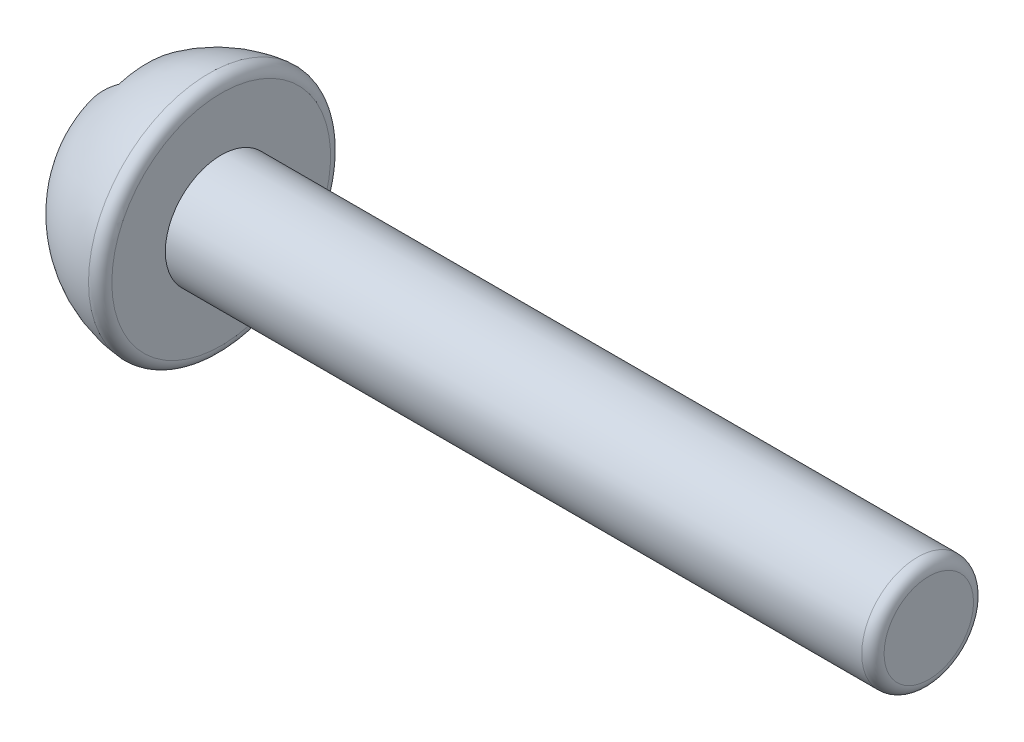
SolidWorks part; units mm, degrees
ref_plane "Front Plane" through (0, 0, 0) normal (0, 0, 1) x (1, 0, 0)
ref_plane "Top Plane" through (0, 0, 0) normal (0, 1, 0) x (1, 0, 0)
ref_plane "Right Plane" through (0, 0, 0) normal (1, 0, 0) x (0, 0, -1)
sketch "Sketch1" plane through (0, 0, 0) normal (0, 0, 1) x (1, 0, 0)
  line L0 (0, 0) -> (57.15, 0)
  line L1 (57.15, 0) -> (57.15, 3.81)
  line L2 (57.15, 3.81) -> (8.89, 3.81)
  line L3 (8.89, 3.81) -> (8.89, 8.255)
  arc A0 (8.89, 8.255) -> (0, 0) centre (8.8673, -0.635) ccw
  dimension "D4" = 8.89
  dimension "D1" = 57.15
  dimension "D2" = 3.81
  dimension "D3" = 4.445
  dimension "D5" = 8.89
revolve "Revolve1" add sketch "Sketch1" angle 360 about L0
sketch "Sketch3" plane through (0, 0, 0) normal (1, 0, 0) x (0, 0, -1)
  line L0 (1.905, -3.6616) -> (1.905, -6.985)
  line L1 (1.905, 6.985) -> (-1.905, 6.985)
  line L2 (1.905, 6.985) -> (1.905, 3.6616)
  line L3 (1.905, -6.985) -> (-1.905, -6.985)
  line L4 (-1.905, 6.985) -> (-1.905, 3.6616)
  line L5 (1.905, 6.985) -> (-1.905, -6.985) construction
  line L6 (1.905, -6.985) -> (-1.905, 6.985) construction
  line L7 (-1.905, -3.6616) -> (-1.905, -6.985)
  arc A2 (-1.905, 3.6616) -> (-1.905, -3.6616) centre (0.6151, 0) ccw
  arc A3 (1.905, 3.6616) -> (1.905, -3.6616) centre (-0.6151, 0) cw
  point P0 (0, 0)
  dimension "D3" = 4.445
  dimension "D1" = 13.97
  dimension "D2" = 3.81
extrude "Cut-Extrude1" cut sketch "Sketch3" along normal blind 3.81
fillet "Fillet1" radius 0.762 2 edges at (57.15, 0, 3.81) (8.89, 0, 8.255)
scale "Scale1" scale about centroid uniform scaling yes scale factor 3
scale "Scale2" [suppressed]
